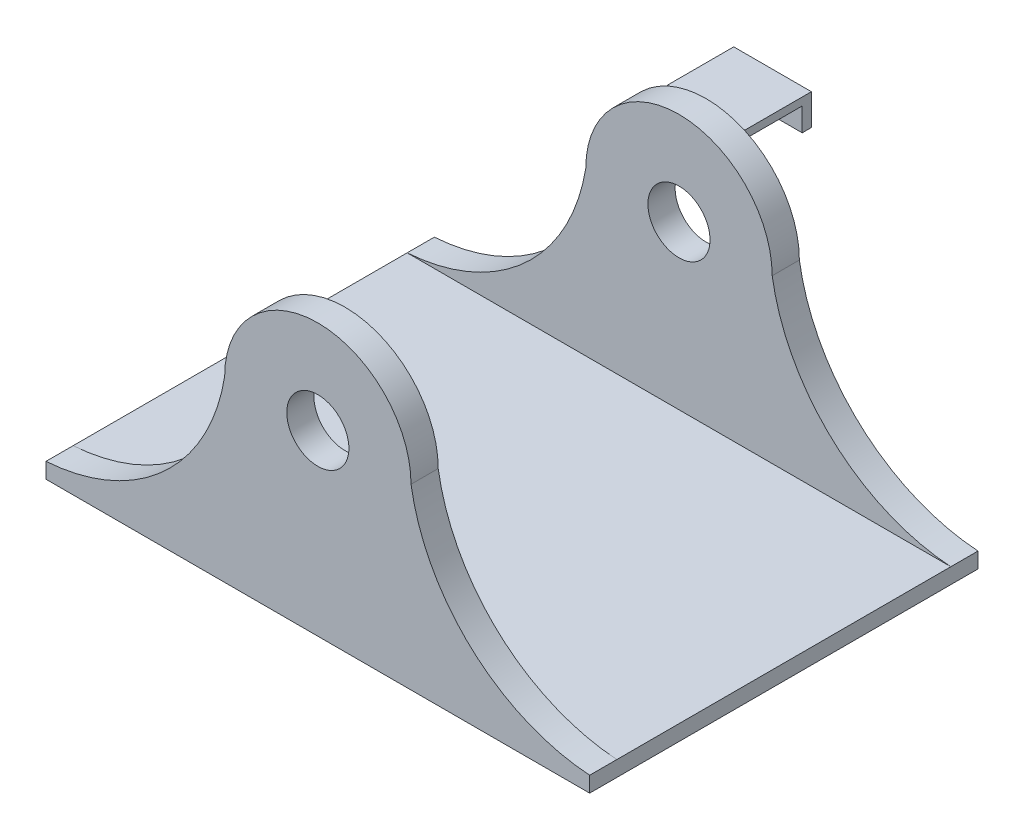
SolidWorks part; units mm, degrees
ref_plane "Front Plane" through (0, 0, 0) normal (0, 0, 1) x (1, 0, 0)
ref_plane "Top Plane" through (0, 0, 0) normal (0, 1, 0) x (1, 0, 0)
ref_plane "Right Plane" through (0, 0, 0) normal (1, 0, 0) x (0, 0, -1)
sketch "Sketch1" plane through (0, 0, 0) normal (0, 0, 1) x (1, 0, 0)
  line L0 (0, 34.9436) -> (0, 26.9436)
  line L2 (-35, 2) -> (-35, 0)
  line L3 (-35, 0) -> (0, 0)
  line L5 (0, 18.9436) -> (0, 0)
  arc A0 (0, 26.9436) -> (0, 18.9436) centre (0, 22.9436) ccw
  arc A1 (0, 34.9436) -> (-12, 22.9436) centre (0, 22.9436) ccw
  arc A2 (-12, 22.9436) -> (-35, 2) centre (-36.6779, 26.9436) cw
  point P1 (0, 0)
  point P3 (-36.9899, 18.7193)
  point P5 (-35.8245, 22.4801)
  point P6 (0, 0)
  point P8 (0, 0)
  point P15 (0, 0)
  point P16 (0, 26.8502)
  point P17 (0, 0)
  dimension "D1" = 4
  dimension "D2" = 8
  dimension "D3" = 25
  dimension "D4" = 2
  dimension "D5" = 35
extrude "Boss-Extrude1" add sketch "Sketch1" along normal blind 50
mirror "Mirror1" about plane through (0, 18.9436, 50) normal (-1, 0, 0) of "Boss-Extrude1"
sketch "Sketch3" plane through (0, 0, 0) normal (1, 0, 0) x (0, 0, -1)
  line L0 (-50, 2) -> (0, 2) construction
  line L1 (-46.5, 43.4678) -> (-3.5, 43.4678)
  line L2 (-46.5, 43.4678) -> (-46.5, 2)
  line L3 (-46.5, 2) -> (-3.5, 2)
  line L4 (-3.5, 43.4678) -> (-3.5, 2)
  line L5 (-50, 34.9436) -> (-46.5, 34.9436) construction
  line L6 (0, 34.9436) -> (-50, 34.9436) construction
  line L7 (-3.5, 34.9436) -> (0, 34.9436) construction
  dimension "D1" = 43
extrude "Cut-Extrude1" cut sketch "Sketch3" against normal through all both and the other way through all
ref_plane "Plane1" through (0, 0, 0) normal (-1, 0, 0) x (0, 0, 1)
sketch "Sketch5" plane through (0, 0, 0) normal (-1, 0, 0) x (0, 0, 1)
  line L0 (-7.3659, 6.54) -> (-7.3659, 1.1841)
  line L1 (0, 0) -> (-8.55, 0)
  line L2 (0, 0) -> (0, 1.1841)
  line L3 (-7.3659, 6.54) -> (-8.55, 6.54)
  line L4 (-8.55, 0) -> (-8.55, 6.54)
  line L5 (-7.3659, 1.1841) -> (0, 1.1841)
  line L6 (0, 34.9436) -> (0, 22.9436) construction
  line L8 (0, 32.9436) -> (0, 33.9436)
  line L9 (0, 33.9436) -> (-8.55, 33.9436)
  line L11 (0, 32.9436) -> (-7.3659, 32.9436)
  line L13 (-7.3659, 32.9436) -> (-7.3659, 29.9436)
  line L14 (-7.3659, 29.9436) -> (-8.55, 29.9436)
  line L15 (-8.55, 33.9436) -> (-8.55, 29.9436)
  point P10 (0, 0)
  point P13 (0, 0)
  point P16 (0, 0)
  point P17 (0, 0)
  point P19 (0, 0)
  dimension "D1" = 8.55
  dimension "D2" = 6.54
  dimension "D3" = 7.3659
  dimension "D4" = 4
  dimension "D5" = 1
  dimension "D6" = 1
extrude "Boss-Extrude3" add sketch "Sketch5" along normal blind 5 and the other way blind 5
sketch "Sketch6" plane through (0, 0, -8.55) normal (0, 0, -1) x (-1, 0, 0)
  line L0 (0, -1.1) -> (0, 1.1) construction
  line L1 (-5, 0) -> (5, 0) construction
  line L4 (-5, 29.9436) -> (5, 29.9436) construction
  circle A0 centre (0, 3.88) radius 1
  circle A1 centre (0, 31.6904) radius 1
  point P8 (0, 0)
  point P9 (0, 27.189)
  point P10 (0, 0)
  point P11 (0, 31.3604)
  dimension "D1" = 2
  dimension "D2" = 3.88
  dimension "D3" = 1.7468
extrude "Cut-Extrude2" cut sketch "Sketch6" against normal up to next
